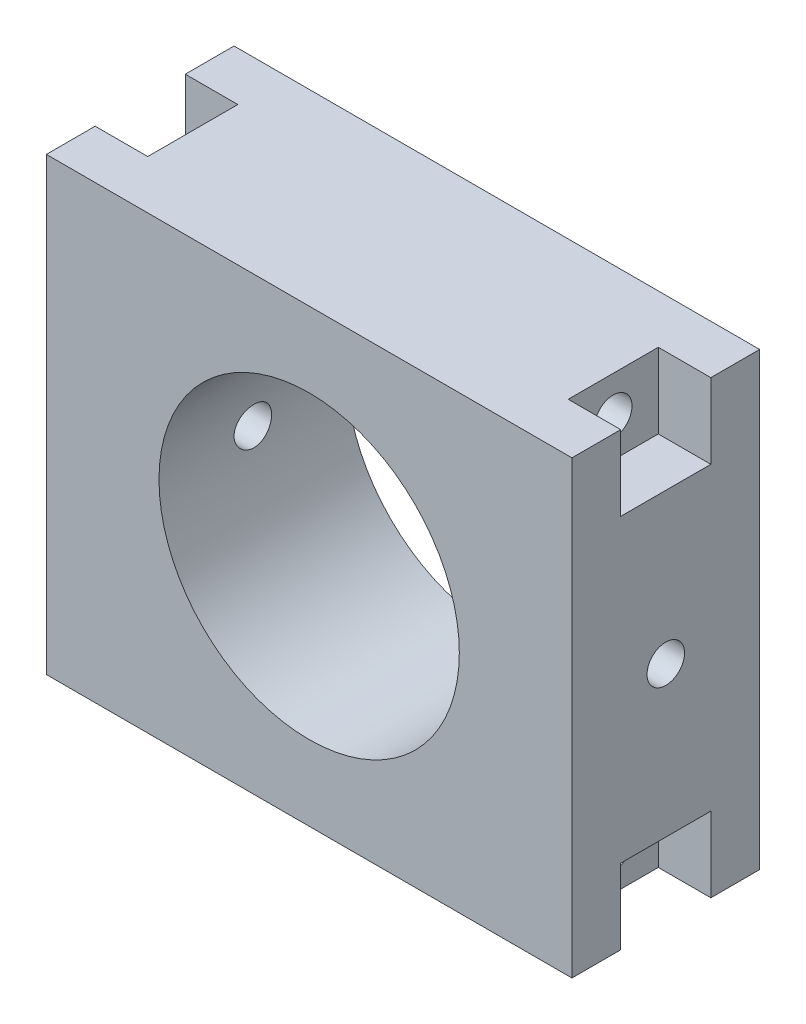
SolidWorks part; units mm, degrees
ref_plane "Front Plane" through (0, 0, 0) normal (0, 0, 1) x (1, 0, 0)
ref_plane "Top Plane" through (0, 0, 0) normal (0, 1, 0) x (1, 0, 0)
ref_plane "Right Plane" through (0, 0, 0) normal (1, 0, 0) x (0, 0, -1)
sketch "Sketch1" plane through (0, 0, 0) normal (0, 0, 1) x (1, 0, 0)
  line L0 (0, 0) -> (0, 191362.0965) construction
  line L1 (0, 0) -> (191362.0965, 0) construction
  line L2 (-25, 0) -> (-35, 0)
  line L3 (-35, -30) -> (-35, 30)
  line L4 (-35, 30) -> (35, 30)
  line L5 (25, 0) -> (35, 0)
  line L6 (35, -30) -> (35, 30)
  line L7 (-35, -30) -> (35, -30)
  circle A0 centre (0, 0) radius 20
  point P13 (0, 30)
  dimension "D1" = 20
  dimension "D2" = 70
  dimension "D3" = 30
extrude "Boss-Extrude1" add sketch "Sketch1" along normal blind 25 contours A0 L5 L6 L4 L3 L2 | A0 L2 L3 L7 L6 L5
sketch "Sketch2" plane through (35, 0, 0) normal (1, 0, 0) x (0, 0, -1)
  line L0 (-12.5, 30) -> (-12.5, -30) construction
  line L1 (-25, 30) -> (0, 30) construction
  line L3 (-25, 30) -> (0, 30) construction
  line L4 (-25, -30) -> (0, -30) construction
  line L5 (0, 0) -> (-25, 0) construction
  line L6 (-25, -30) -> (-25, 30) construction
  circle A0 centre (-12.5, 25) radius 2.5
  circle A1 centre (-12.5, -25) radius 2.5
  circle A2 centre (-12.5, 0) radius 2.5
  dimension "D1" = 5
  dimension "D4" = 5
  dimension "D2" = 5
  dimension "D3" = 5
extrude "Cut-Extrude1" cut sketch "Sketch2" against normal through all
fillet "Fillet1" [suppressed] radius 20
sketch "Sketch3" plane through (0, 30, 0) normal (0, 1, 0) x (1, 0, 0)
  line L0 (-35, -25) -> (-35, 0) construction
  line L1 (-35, -6.5) -> (-28, -6.5)
  line L2 (-35, -6.5) -> (-35, -18.5)
  line L3 (-35, -18.5) -> (-28, -18.5)
  line L4 (-28, -6.5) -> (-28, -18.5)
  line L5 (-35, -12.5) -> (35, -12.5) construction
  line L6 (35, -25) -> (35, 0) construction
  line L7 (0, 0) -> (0, -25) construction
  line L8 (-35, -25) -> (35, -25) construction
  line L9 (35, -6.5) -> (35, -18.5)
  line L10 (35, -18.5) -> (28, -18.5)
  line L11 (28, -6.5) -> (28, -18.5)
  line L12 (35, -6.5) -> (28, -6.5)
  line L14 (-28, -15) -> (28, -15)
  line L15 (-28, -15) -> (-28, -10)
  line L16 (-28, -10) -> (28, -10)
  line L17 (28, -15) -> (28, -10)
  point P19 (0, -12.5)
  line M10 (-35, 0) -> (-35, -25)
  dimension "D1" = 7
  dimension "D2" = 12
  dimension "D3" = 5
extrude "Cut-Extrude2" cut sketch "Sketch3" against normal blind 10 contours L4 L1 L3 M10 | L9 L10 L11 L12
mirror "Mirror1" about plane through (0, 0, 0) normal (0, 1, 0) of "Cut-Extrude2"
